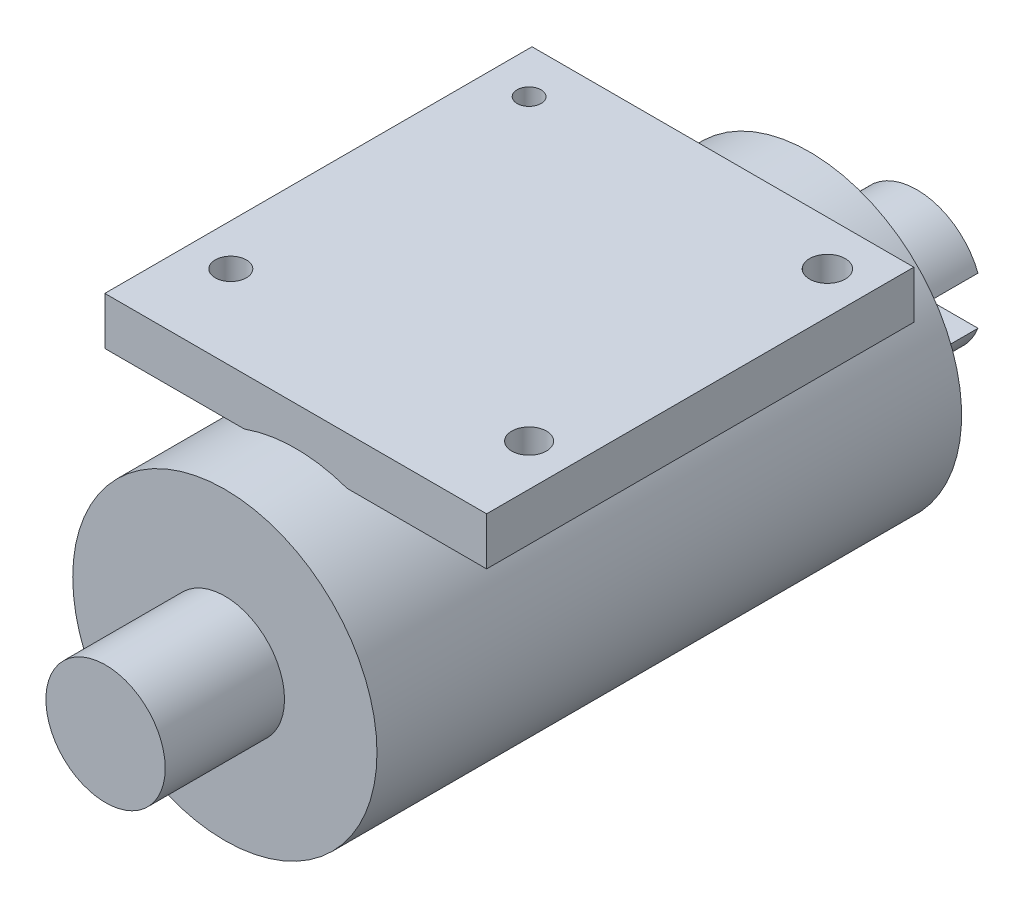
SolidWorks part; units mm, degrees
ref_plane "Front Plane" through (0, 0, 0) normal (0, 0, 1) x (1, 0, 0)
ref_plane "Top Plane" through (0, 0, 0) normal (0, 1, 0) x (1, 0, 0)
ref_plane "Right Plane" through (0, 0, 0) normal (1, 0, 0) x (0, 0, -1)
sketch "Sketch1" plane through (0, 0, 0) normal (0, 0, 1) x (1, 0, 0)
  circle A0 centre (0, 0) radius 25.5
  dimension "D1" = 51
extrude "Boss-Extrude1" add sketch "Sketch1" along normal blind 116
sketch "Sketch3" plane through (0, 0, 0) normal (0, 0, -1) x (-1, 0, 0)
  circle A0 centre (0, 0) radius 11
  dimension "D1" = 22
extrude "Cut-Extrude2" cut sketch "Sketch3" against normal blind 18 flip side to cut
sketch "Sketch4" plane through (0, 0, 0) normal (0, 0, -1) x (-1, 0, 0)
  line L1 (-20.3856, -4) -> (14.9337, -4)
  line L2 (-20.3856, -4) -> (-20.3856, 4)
  line L3 (-20.3856, 4) -> (14.9337, 4)
  line L4 (14.9337, -4) -> (14.9337, 4)
  dimension "D1" = 4
  dimension "D2" = 8
extrude "Cut-Extrude3" cut sketch "Sketch4" against normal blind 12
ref_plane "Plane1" through (0, 32, 0) normal (0, 1, 0) x (-1, 0, 0)
sketch "Sketch5" plane through (0, 32, 0) normal (0, 1, 0) x (-1, 0, 0)
  line L0 (0, 116) -> (0, 104.1192) construction
  line L1 (32, 32.5113) -> (-32, 32.5113)
  line L2 (32, 32.5113) -> (32, 104.1192)
  line L3 (32, 104.1192) -> (-32, 104.1192)
  line L4 (-32, 32.5113) -> (-32, 104.1192)
  line L5 (25.5, 116) -> (-25.5, 116) construction
  line L6 (-25, 40) -> (25, 40) construction
  line L7 (0, 104.1192) -> (0, 40) construction
  line L8 (-10.247, 0) -> (10.247, 0) construction
  circle A0 centre (-25, 90) radius 2.9103
  circle A1 centre (-25, 40) radius 2.9878
  circle A2 centre (25, 90) radius 2.6105
  circle A3 centre (25, 40) radius 2.007
  dimension "D2" = 50
  dimension "D3" = 50
  dimension "D4" = 40
  dimension "D1" = 64
extrude "Boss-Extrude2" add sketch "Sketch5" against normal blind 8
sketch "Sketch6" plane through (0, 0, 116) normal (0, 0, 1) x (1, 0, 0)
  circle A0 centre (0, 0) radius 10
  dimension "D1" = 20
extrude "Boss-Extrude3" add sketch "Sketch6" along normal blind 20
